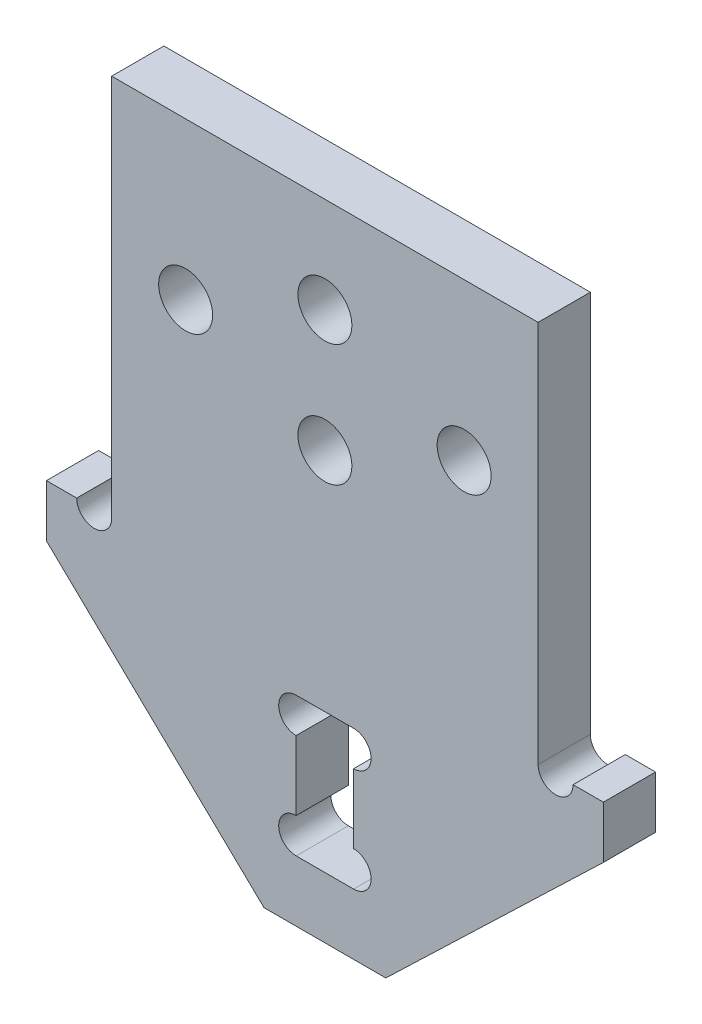
SolidWorks part; units mm, degrees
material "Thornel Mat VMA"
ref_plane "前视基准面" through (0, 0, 0) normal (0, 0, 1) x (1, 0, 0)
ref_plane "上视基准面" through (0, 0, 0) normal (0, 1, 0) x (1, 0, 0)
ref_plane "右视基准面" through (0, 0, 0) normal (1, 0, 0) x (0, 0, -1)
sketch "草图1" plane through (0, 0, 0) normal (0, 0, 1) x (1, 0, 0)
  line L0 (-12.25, -11) -> (-16, -11)
  line L1 (12.25, -11) -> (-12.25, -11) construction
  line L2 (12.25, -11) -> (12.25, 11)
  line L3 (12.25, 11) -> (-12.25, 11)
  line L4 (-12.25, -11) -> (-12.25, 11)
  line L5 (12.25, -11) -> (-12.25, 11) construction
  line L6 (12.25, 11) -> (-12.25, -11) construction
  line L7 (-16, -11) -> (-16, -26) construction
  line L8 (-16, -26) -> (16, -26) construction
  line L9 (0, 0) -> (0, -12.2289) construction
  line L10 (16, -11) -> (16, -26) construction
  line L11 (12.25, -11) -> (16, -11)
  line L12 (-16, -14) -> (-3.5, -26)
  line L13 (1.65, -22.5) -> (-1.65, -22.5)
  line L14 (1.65, -22.5) -> (1.65, -14.5)
  line L15 (1.65, -14.5) -> (-1.65, -14.5)
  line L16 (-1.65, -22.5) -> (-1.65, -14.5)
  line L17 (1.65, -22.5) -> (-1.65, -14.5) construction
  line L18 (1.65, -14.5) -> (-1.65, -22.5) construction
  line L19 (16, -14) -> (3.5, -26)
  line L20 (-16, -11) -> (-16, -14)
  line L21 (-3.5, -26) -> (3.5, -26)
  line L22 (16, -14) -> (16, -11)
  line L23 (-8, 2) -> (-1.5578, 2) construction
  circle A0 centre (-13.255, -11) radius 1.005
  circle A1 centre (13.255, -11) radius 1.005
  circle A2 centre (1.65, -15.505) radius 1.005
  circle A3 centre (-1.65, -15.505) radius 1.005
  circle A4 centre (-1.65, -21.495) radius 1.005
  circle A5 centre (1.65, -21.495) radius 1.005
  circle A6 centre (0, 5.5) radius 1.55
  circle A7 centre (0, -1.5) radius 1.55
  circle A8 centre (8, 2) radius 1.55
  circle A9 centre (-8, 2) radius 1.55
  point P0 (0, 0)
  point P17 (0, -18.5)
  point P33 (0, 1.5)
  dimension "D5" = 2.01
  dimension "D11" = 3.1
  dimension "D1" = 24.5
  dimension "D2" = 22
  dimension "D3" = 15
  dimension "D4" = 32
  dimension "D6" = 3.3
  dimension "D7" = 8
  dimension "D8" = 7.5
  dimension "D9" = 3
  dimension "D10" = 7
  dimension "D12" = 7
  dimension "D13" = 8
  dimension "D14" = 13
extrude "凸台-拉伸1" add sketch "草图1" along normal blind 3
